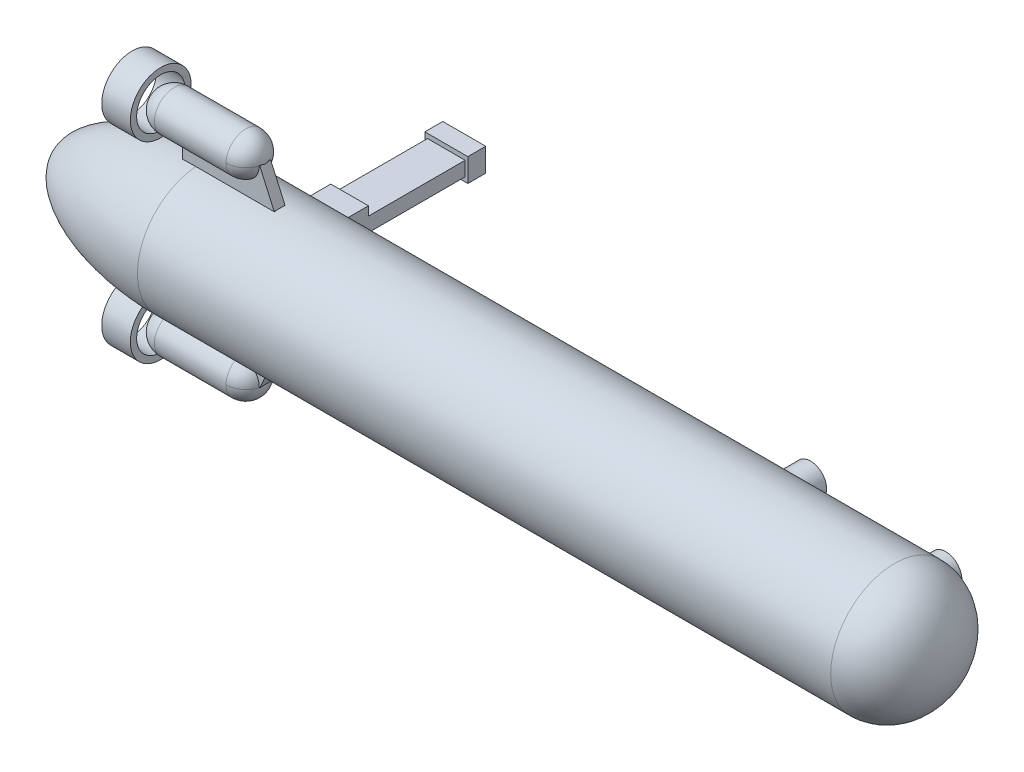
SolidWorks part; units mm, degrees
ref_plane "Front Plane" through (0, 0, 0) normal (0, 0, 1) x (1, 0, 0)
ref_plane "Top Plane" through (0, 0, 0) normal (0, 1, 0) x (1, 0, 0)
ref_plane "Right Plane" through (0, 0, 0) normal (1, 0, 0) x (0, 0, -1)
sketch "Sketch1" plane through (0, 0, 0) normal (1, 0, 0) x (0, 0, -1)
  circle A0 centre (0, 0) radius 115
extrude "Boss-Extrude2" add sketch "Sketch1" along normal blind 761.29
sketch "Sketch2" plane through (0, 0, 0) normal (1, 0, 0) x (0, 0, -1)
  circle A0 centre (0, 0) radius 115
extrude "Boss-Extrude3" add sketch "Sketch2" against normal blind 487.1
sketch "Sketch3" plane through (0, 0, 0) normal (0, 1, 0) x (1, 0, 0)
  line L0 (761.29, 0) -> (761.29, 50000) construction
  line L1 (761.29, -115) -> (761.29, 115) construction
  line L2 (761.29, 0) -> (858.06, 0)
  line L3 (761.29, 0) -> (761.29, 115)
  ellipse E0 centre (761.29, 0) end of major axis (761.29, 115) minor radius 96.77 (761.29, 115) -> (858.06, 0) cw
  point P4 (761.29, 0)
  dimension "D1" = 96.77
revolve "Revolve1" add sketch "Sketch3" angle 360 about L2
sketch "Sketch4" plane through (0, 0, 0) normal (0, 1, 0) x (1, 0, 0)
  line L0 (858.06, 0) -> (-487.1, 0) construction
  line L1 (-487.1, 115) -> (-487.1, -115) construction
  line L2 (-487.1, 0) -> (-741.94, 0)
  line L3 (-487.1, 0) -> (-487.1, -115)
  ellipse E0 centre (-487.1, 0) end of major axis (-741.94, 0) minor radius 115 (-487.1, -115) -> (-741.94, 0) cw
revolve "Revolve2" add sketch "Sketch4" angle 360 about L0
sketch "Sketch5" plane through (0, 0, 0) normal (0, 0, 1) x (1, 0, 0)
  line L0 (0, 0) -> (440, 0) construction
  circle A0 centre (440, 0) radius 29
extrude "Boss-Extrude4" add sketch "Sketch5" against normal blind 170
sketch "Sketch6" plane through (0, 0, 0) normal (0, 0, 1) x (1, 0, 0)
  line L0 (0, 0) -> (703, 0) construction
  circle A0 centre (703, 0) radius 29
extrude "Boss-Extrude5" add sketch "Sketch6" against normal blind 150.5
sketch "Sketch7" plane through (0, 0, 0) normal (0, 0, 1) x (1, 0, 0)
  line L0 (0, 0) -> (-390, 0) construction
  line L2 (-423.875, -29) -> (-356.125, -29)
  line L3 (-423.875, -29) -> (-423.875, 29)
  line L4 (-423.875, 29) -> (-356.125, 29)
  line L5 (-356.125, -29) -> (-356.125, 29)
  line L6 (-423.875, -29) -> (-356.125, 29) construction
  line L7 (-423.875, 29) -> (-356.125, -29) construction
  dimension "D1" = 67.75
  dimension "D2" = 58
extrude "Boss-Extrude6" add sketch "Sketch7" against normal blind 170
ref_plane "Plane2" through (0, 0, -170) normal (0, 0, -1) x (-1, 0, 0)
sketch "Sketch8" plane through (0, 0, -170) normal (0, 0, -1) x (-1, 0, 0)
  line L0 (423.875, 29) -> (356.125, -29) construction
  line L1 (423.875, 29) -> (423.875, -29) construction
  line L2 (356.125, 12.9) -> (423.875, 12.9)
  line L3 (356.125, 12.9) -> (356.125, -12.9)
  line L4 (356.125, -12.9) -> (423.875, -12.9)
  line L5 (423.875, 12.9) -> (423.875, -12.9)
  line L6 (356.125, 12.9) -> (423.875, -12.9) construction
  line L7 (356.125, -12.9) -> (423.875, 12.9) construction
  point P4 (390, 0)
  dimension "D1" = 25.8
extrude "Boss-Extrude7" add sketch "Sketch8" along normal blind 174.2
ref_plane "Plane3" through (0, 0, -344.2) normal (0, 0, -1) x (-1, 0, 0)
sketch "Sketch9" plane through (0, 0, -344.2) normal (0, 0, -1) x (-1, 0, 0)
  line L0 (423.875, 12.9) -> (356.125, -12.9) construction
  line L2 (428.7, 21) -> (351.3, 21)
  line L3 (428.7, 21) -> (428.7, -21)
  line L4 (428.7, -21) -> (351.3, -21)
  line L5 (351.3, 21) -> (351.3, -21)
  line L6 (428.7, 21) -> (351.3, -21) construction
  line L7 (428.7, -21) -> (351.3, 21) construction
  point P4 (390, 0)
  dimension "D1" = 77.4
  dimension "D2" = 42
extrude "Boss-Extrude8" add sketch "Sketch9" along normal blind 32.26
sketch "Sketch10" plane through (0, 0, 0) normal (0, 0, 1) x (1, 0, 0)
  line L0 (0, 0) -> (-346, 0) construction
  line L1 (-346, -115) -> (-346, 115)
  line L2 (761.29, 115) -> (-487.1, 115) construction
  line L3 (-346, 0) -> (-511, 0) construction
  line L4 (-511, -173) -> (-511, 173)
  line L5 (-511, 173) -> (-372, 173)
  line L6 (-372, 173) -> (-346, 115)
  line L7 (-511, -173) -> (-372, -173)
  line L8 (-372, -173) -> (-346, -115)
  point P8 (-346, 0)
  point P12 (-511, 0)
extrude "Boss-Extrude9" add sketch "Sketch10" along normal blind 9.75 and the other way blind 9.75
ref_plane "Plane4" through (-372, 0, 0) normal (1, 0, 0) x (0, 0, -1)
ref_plane "Plane5" through (-407, 0, 0) normal (1, 0, 0) x (0, 0, -1)
sketch "Sketch11" plane through (-407, 0, 0) normal (1, 0, 0) x (0, 0, -1)
  line L0 (9.75, 173) -> (-9.75, 173) construction
  line L1 (9.75, -173) -> (-9.75, -173) construction
  circle A0 centre (0, 173) radius 35.5
  circle A1 centre (0, -173) radius 35.5
extrude "Boss-Extrude10" add sketch "Sketch11" against normal blind 129
ref_plane "Plane6" through (0, 173, 0) normal (0, 1, 0) x (1, 0, 0)
sketch "Sketch12" plane through (0, 173, 0) normal (0, 1, 0) x (1, 0, 0)
  line L1 (-407, -9.75) -> (-407, 9.75) construction
  line L2 (-407, 35.5) -> (-407, 0)
  line L3 (-407, 0) -> (-371.5, 0)
  line L4 (-407, 35.5) -> (-536, 35.5) construction
  line L5 (-536, 0) -> (-536, 35.5)
  line L6 (-536, 35.5) -> (-536, -35.5) construction
  line L7 (-536, 0) -> (-571.5, 0)
  line L8 (-536, 0) -> (-407, 0) construction
  arc A0 (-371.5, 0) -> (-407, 35.5) centre (-407, 0) ccw
  arc A1 (-571.5, 0) -> (-536, 35.5) centre (-536, 0) cw
revolve "Revolve6" add sketch "Sketch12" angle 360 about L8
ref_plane "Plane7" through (0, -173, 0) normal (0, -1, 0) x (-1, 0, 0)
sketch "Sketch13" plane through (0, -173, 0) normal (0, -1, 0) x (-1, 0, 0)
  line L0 (407, 0) -> (371.5, 0)
  line L1 (407, 35.5) -> (407, -35.5) construction
  line L2 (407, 0) -> (407, -35.5)
  line L3 (536, 0) -> (571.5, 0)
  line L4 (536, -35.5) -> (536, 35.5) construction
  line L5 (536, 0) -> (536, -35.5)
  arc A0 (407, -35.5) -> (371.5, 0) centre (407, 0) cw
  arc A1 (571.5, 0) -> (536, -35.5) centre (536, 0) cw
revolve "Revolve7" add sketch "Sketch13" angle 360 about L0
ref_plane "Plane8" through (-560, 0, 0) normal (1, 0, 0) x (0, 0, -1)
sketch "Sketch14" plane through (-560, 0, 0) normal (1, 0, 0) x (0, 0, -1)
  line L0 (-35.5, 173) -> (35.5, 173) construction
  line L1 (-35.5, -173) -> (35.5, -173) construction
  arc A0 (9.75, 138.8652) -> (-9.75, 138.8652) centre (0, 173) ccw construction
  circle A1 centre (0, 173) radius 54.84
  circle A2 centre (0, 173) radius 43.5
  arc A3 (-9.75, -138.8652) -> (9.75, -138.8652) centre (0, -173) ccw construction
  circle A4 centre (0, -173) radius 43.5
  circle A5 centre (0, -173) radius 54.84
extrude "Boss-Extrude11" add sketch "Sketch14" against normal blind 51.5 separate body
